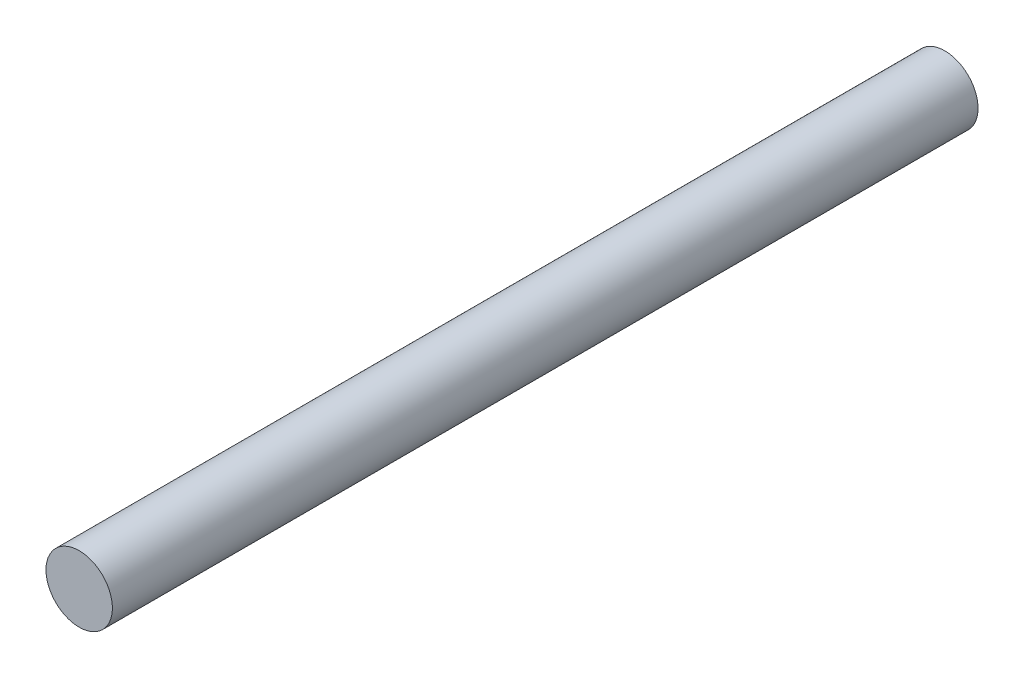
SolidWorks part; units mm, degrees
ref_plane "Front Plane" through (0, 0, 0) normal (0, 0, 1) x (1, 0, 0)
ref_plane "Top Plane" through (0, 0, 0) normal (0, 1, 0) x (1, 0, 0)
ref_plane "Right Plane" through (0, 0, 0) normal (1, 0, 0) x (0, 0, -1)
sketch "Sketch1" plane through (0, 0, 0) normal (0, 0, 1) x (1, 0, 0)
  circle A0 centre (0, 0) radius 2.921
  dimension "D1" = 5.842
extrude "Boss-Extrude1" add sketch "Sketch1" along normal blind 76.2
